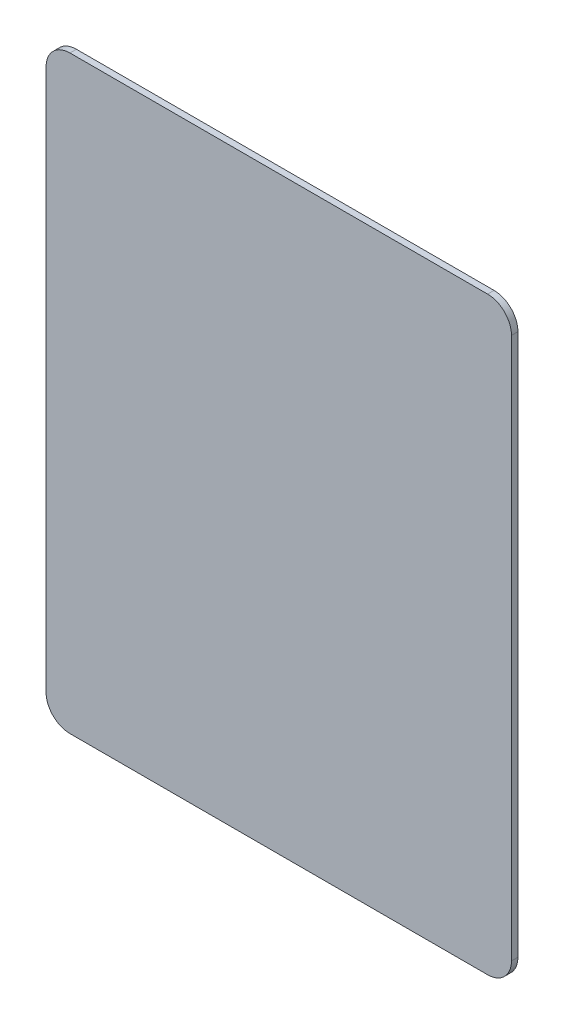
SolidWorks part; units mm, degrees
ref_plane "Front Plane" through (0, 0, 0) normal (0, 0, 1) x (1, 0, 0)
ref_plane "Top Plane" through (0, 0, 0) normal (0, 1, 0) x (1, 0, 0)
ref_plane "Right Plane" through (0, 0, 0) normal (1, 0, 0) x (0, 0, -1)
sketch "Sketch2" plane through (0, 0, 0) normal (0, 0, 1) x (1, 0, 0)
  line L1 (61.2595, 237) -> (236.2595, 237)
  line L3 (61.2595, -10) -> (236.2595, -10)
  line L5 (246.2595, 227) -> (246.2595, 0)
  line L11 (51.2595, 0) -> (51.2595, 227)
  arc A0 (51.2595, 0) -> (61.2595, -10) centre (61.2595, 0) ccw
  arc A1 (236.2595, -10) -> (246.2595, 0) centre (236.2595, 0) ccw
  arc A2 (236.2595, 237) -> (246.2595, 227) centre (236.2595, 227) cw
  arc A3 (61.2595, 237) -> (51.2595, 227) centre (61.2595, 227) ccw
  point P19 (246.2595, 237)
  point P22 (51.2595, 237)
  dimension "D1" = 10
  dimension "D3" = 195
  dimension "D8" = 247
extrude "Boss-Extrude1" add sketch "Sketch2" along normal blind 2.7
